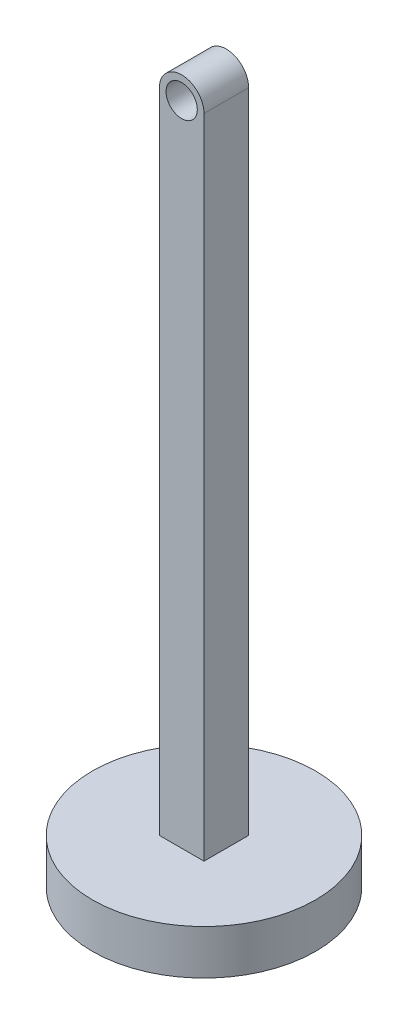
SolidWorks part; units mm, degrees
ref_plane "Front Plane" through (0, 0, 0) normal (0, 0, 1) x (1, 0, 0)
ref_plane "Top Plane" through (0, 0, 0) normal (0, 1, 0) x (1, 0, 0)
ref_plane "Right Plane" through (0, 0, 0) normal (1, 0, 0) x (0, 0, -1)
sketch "Sketch1" plane through (0, 0, 0) normal (0, 0, 1) x (1, 0, 0)
  line L2 (-5, 0) -> (-5, -150)
  line L3 (-5, -150) -> (5, -150)
  line L4 (5, 0) -> (5, -150)
  circle A0 centre (0, 0) radius 3.5
  arc A1 (-5, 0) -> (5, 0) centre (0, 0) cw
  dimension "D1" = 150
  dimension "D2" = 10
  dimension "D3" = 7
extrude "Boss-Extrude1" add sketch "Sketch1" along normal blind 10 contours L2 L3 L4 A1 | A0
sketch "Sketch2" plane through (0, -150, 0) normal (0, -1, 0) x (1, 0, 0)
  line L0 (-5, 10) -> (-5, 0) construction
  circle A0 centre (0, 5) radius 25
  point P7 (-5, 5)
  dimension "D1" = 50
extrude "Boss-Extrude2" add sketch "Sketch2" along normal mid plane 10
